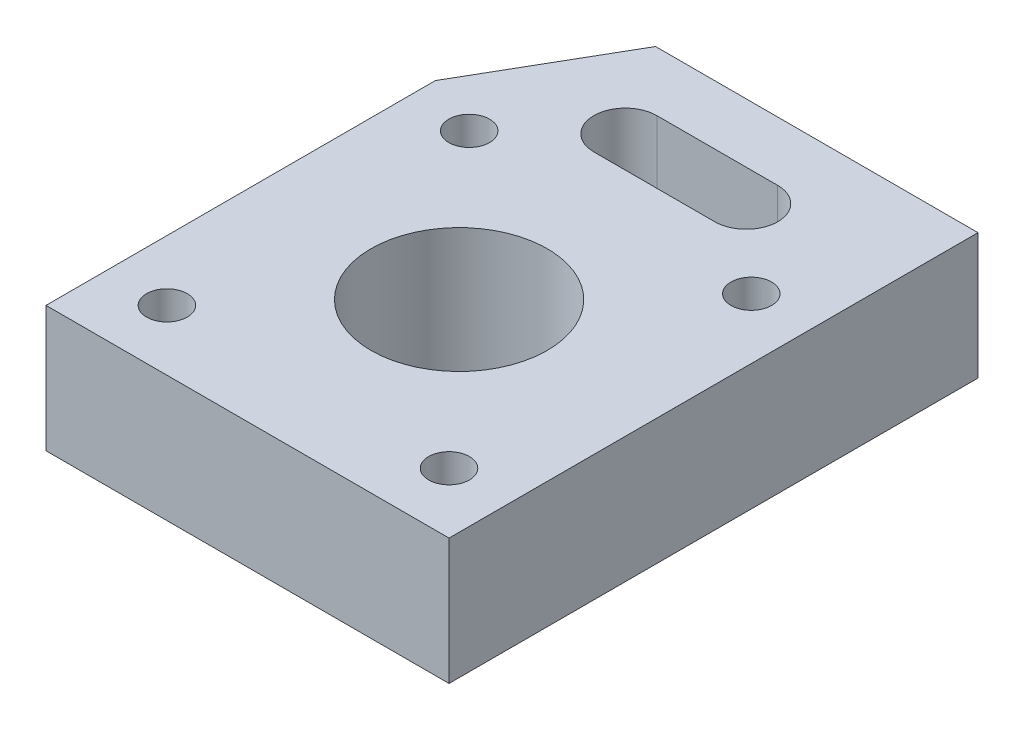
SolidWorks part; units mm, degrees
ref_plane "Front Plane" through (0, 0, 0) normal (0, 0, 1) x (1, 0, 0)
ref_plane "Top Plane" through (0, 0, 0) normal (0, 1, 0) x (1, 0, 0)
ref_plane "Right Plane" through (0, 0, 0) normal (1, 0, 0) x (0, 0, -1)
sketch "Sketch1" plane through (0, 0, 0) normal (0, 1, 0) x (1, 0, 0)
  line L0 (-30.48, 80.01) -> (50.8, 80.01)
  line L1 (50.8, 80.01) -> (50.8, -53.34)
  line L2 (50.8, -53.34) -> (-50.8, -53.34)
  line L3 (-50.8, -53.34) -> (-50.8, 44.8147)
  line L4 (-50.8, 44.8147) -> (-30.48, 80.01)
  line L5 (-15.24, 65.0875) -> (15.24, 65.0875)
  line L7 (15.24, 49.2125) -> (-15.24, 49.2125)
  circle A5 centre (0, 0) radius 22.225
  circle A7 centre (35.56, 38.1) radius 5.1308
  circle A8 centre (-35.56, 38.1) radius 5.1308
  circle A9 centre (-35.56, -38.1) radius 5.1308
  circle A10 centre (35.56, -38.1) radius 5.1308
  arc A11 (15.24, 49.2125) -> (15.24, 65.0875) centre (15.24, 57.15) ccw
  arc A12 (-15.24, 65.0875) -> (-15.24, 49.2125) centre (-15.24, 57.15) ccw
  dimension "D1" = 101.6
  dimension "D6" = 60
  dimension "D2" = 44.45
  dimension "D10" = 10.2616
  dimension "D11" = 10.2616
  dimension "D13" = 10.2616
  dimension "D14" = 10.2616
  dimension "D20" = 15.875
  dimension "D21" = 15.875
  dimension "D3" = 50.8
  dimension "D4" = 53.34
  dimension "D5" = 133.35
  dimension "D7" = 30.48
  dimension "D8" = 38.1
  dimension "D9" = 35.56
  dimension "D12" = 35.56
  dimension "D15" = 38.1
  dimension "D16" = 35.56
  dimension "D17" = 35.56
  dimension "D18" = 38.1
  dimension "D19" = 38.1
  dimension "D22" = 15.24
  dimension "D23" = 15.24
  dimension "D24" = 57.15
extrude "Boss-Extrude1" add sketch "Sketch1" along normal blind 31.75
